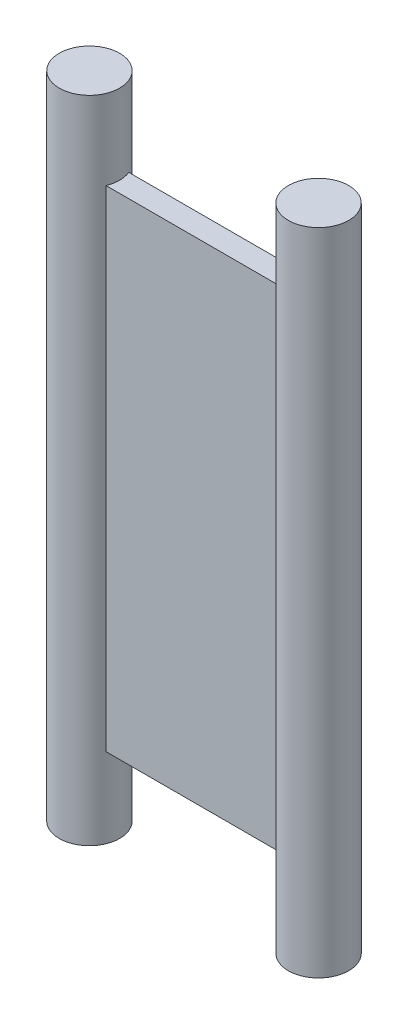
SolidWorks part; units mm, degrees
ref_plane "Front Plane" through (0, 0, 0) normal (0, 0, 1) x (1, 0, 0)
ref_plane "Top Plane" through (0, 0, 0) normal (0, 1, 0) x (1, 0, 0)
ref_plane "Right Plane" through (0, 0, 0) normal (1, 0, 0) x (0, 0, -1)
sketch "Sketch1" plane through (0, 0, 0) normal (0, 1, 0) x (1, 0, 0)
  line L1 (5.0235, 0.5) -> (-5.0235, 0.5)
  line L2 (5.0235, 0.5) -> (5.0235, -0.5)
  line L3 (5.0235, -0.5) -> (-5.0235, -0.5)
  line L4 (-5.0235, 0.5) -> (-5.0235, -0.5)
  line L5 (5.0235, 0.5) -> (-5.0235, -0.5) construction
  line L6 (5.0235, -0.5) -> (-5.0235, 0.5) construction
  point P0 (0, 0)
  dimension "D1" = 10.047
  dimension "D3" = 1
extrude "Boss-Extrude1" add sketch "Sketch1" along normal blind 21.5
ref_plane "Plane1" through (0, 10.75, 0) normal (0, 1, 0) x (1, 0, 0)
sketch "Sketch2" plane through (0, 10.75, 0) normal (0, 1, 0) x (1, 0, 0)
  line L0 (5.0235, -0.5) -> (5.0235, 0.5) construction
  line L1 (-5.0235, 0.5) -> (-5.0235, -0.5) construction
  line L2 (5.0235, -0.5) -> (5.0235, 0.5) construction
  line L3 (-5.0235, 0.5) -> (-5.0235, -0.5) construction
  circle A0 centre (-5.0235, 0) radius 1.325
  circle A1 centre (5.0235, 0) radius 1.325
  dimension "D1" = 2.65
extrude "Boss-Extrude2" add sketch "Sketch2" along normal mid plane 28.5
